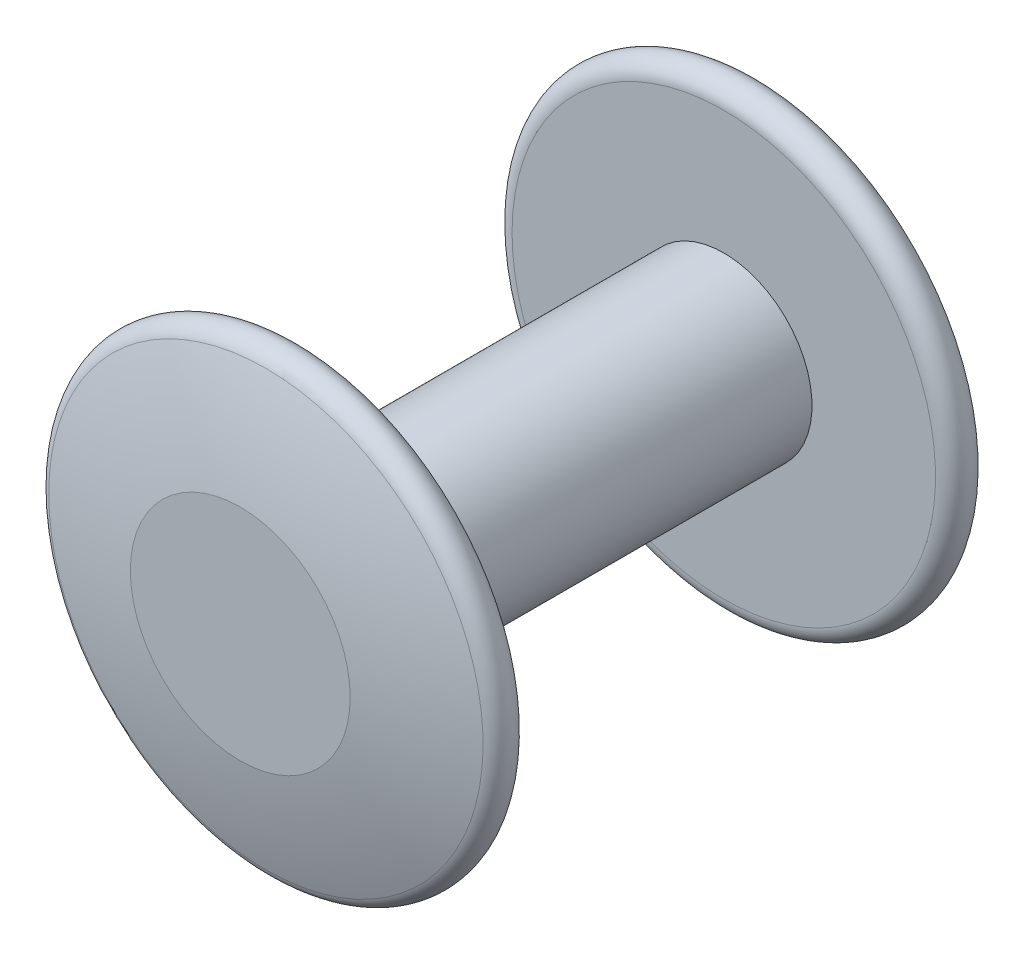
SolidWorks part; units mm, degrees
other "Defeature"
material "201 Annealed Stainless Steel (SS)"
ref_plane "Front Plane" through (0, 0, 0) normal (0, 0, 1) x (1, 0, 0)
ref_plane "Top Plane" through (0, 0, 0) normal (0, 1, 0) x (1, 0, 0)
ref_plane "Right Plane" through (0, 0, 0) normal (1, 0, 0) x (0, 0, -1)
sketch "Sketch2" plane through (0, 0, 0) normal (1, 0, 0) x (0, 0, -1)
  line L0 (7.946, 0) -> (-7.946, 0)
  line L1 (-6, 6) -> (-6, 2.5)
  line L2 (-6, 2.5) -> (6, 2.5)
  line L3 (0, 2.5) -> (0, 0)
  line L4 (6, 6) -> (6, 2.5)
  line L5 (-7.702, 3.1149) -> (-7.702, 0)
  line L6 (-7.702, 0) -> (7.702, 0)
  line L7 (7.702, 0) -> (7.702, 3.1149)
  arc A0 (-7.946, 0) -> (-6.9757, 6.1538) centre (12.054, 0) cw
  arc A1 (-6.9757, 6.1538) -> (-6, 6) centre (-6.5, 6) cw
  arc A2 (6.9757, 6.1538) -> (6, 6) centre (6.5, 6) ccw
  arc A3 (7.946, 0) -> (6.9757, 6.1538) centre (-12.054, 0) ccw
  dimension "D3" = 0.5
  dimension "D4" = 20
  dimension "D1" = 6
  dimension "D2" = 6
  dimension "D5" = 2.5
revolve "Revolve1" add sketch "Sketch2" angle 360 about L0
